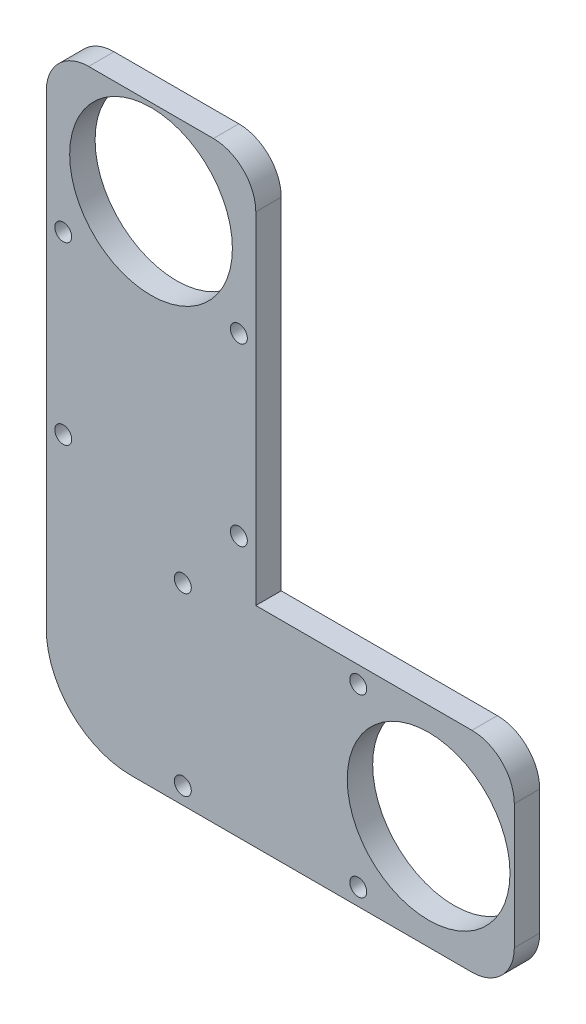
SolidWorks part; units mm, degrees
ref_plane "前视基准面" through (0, 0, 0) normal (0, 0, 1) x (1, 0, 0)
ref_plane "上视基准面" through (0, 0, 0) normal (0, 1, 0) x (1, 0, 0)
ref_plane "右视基准面" through (0, 0, 0) normal (1, 0, 0) x (0, 0, -1)
sketch "草图1" plane through (0, 0, 0) normal (0, 0, 1) x (1, 0, 0)
  line L1 (-1.2093, 0.7424) -> (44.0107, 0.7424)
  line L2 (-1.2093, 0.7424) -> (-1.2093, -23.9776)
  line L3 (-1.2093, -23.9776) -> (44.0107, -23.9776)
  line L4 (44.0107, 0.7424) -> (44.0107, -23.9776)
  circle A0 centre (33.9007, -11.6176) radius 9.6
  circle A1 centre (25.6007, -1.2576) radius 1
  circle A2 centre (4.9007, -1.2576) radius 1
  circle A3 centre (4.9007, -21.9776) radius 1
  circle A4 centre (25.6007, -21.9776) radius 1
  dimension "D3" = 19.2
  dimension "D4" = 2
  dimension "D5" = 2
  dimension "D6" = 2
  dimension "D7" = 2
  dimension "D10" = 20.7
  dimension "D11" = 20.7
  dimension "D13" = 2
  dimension "D15" = 2
  dimension "D1" = 45.22
  dimension "D2" = 24.72
  dimension "D8" = 6.11
  dimension "D9" = 6.11
  dimension "D12" = 2
  dimension "D14" = 2
  dimension "D16" = 10.11
  dimension "D17" = 12.36
extrude "凸台-拉伸1" add sketch "草图1" along normal blind 3
sketch "草图2" plane through (-1.2093, 0, 0) normal (-1, 0, 0) x (0, 0, 1)
  line L4 (0, 0.7424) -> (0, -23.9776)
  line L5 (0, -23.9776) -> (3, -23.9776)
  line L6 (3, -23.9776) -> (3, 0.7424)
  line L7 (3, 0.7424) -> (0, 0.7424)
  line L8 (0, 0.7424) -> (0, -23.9776)
  line L9 (0, -23.9776) -> (3, -23.9776)
  line L10 (3, -23.9776) -> (3, 0.7424)
  line L11 (3, 0.7424) -> (0, 0.7424)
  dimension "D1" = 0
extrude "凸台-拉伸2" add sketch "草图2" along normal blind 10
sketch "草图3" plane through (0, 0.7424, 0) normal (0, 1, 0) x (1, 0, 0)
  line L0 (-11.2093, -3) -> (-11.2093, 0) construction
  line L1 (-11.2093, 0) -> (13.5107, 0)
  line L2 (-11.2093, 0) -> (-11.2093, -3)
  line L3 (-11.2093, -3) -> (13.5107, -3)
  line L4 (13.5107, 0) -> (13.5107, -3)
  line L5 (44.0107, 0) -> (-11.2093, 0) construction
  line L6 (44.0107, -3) -> (-11.2093, -3) construction
  dimension "D1" = 24.72
  dimension "D2" = 0
  dimension "D3" = 0
  dimension "D4" = 0
extrude "凸台-拉伸3" add sketch "草图3" along normal blind 45.22
sketch "草图4" plane through (0, 0, 3) normal (0, 0, 1) x (1, 0, 0)
  line L0 (-11.2093, 45.9624) -> (13.5107, 45.9624) construction
  line L1 (-11.2093, -23.9776) -> (-11.2093, 45.9624) construction
  line L2 (13.5107, 45.9624) -> (13.5107, 0.7424) construction
  circle A0 centre (1.1507, 35.8524) radius 9.6
  circle A1 centre (-9.2093, 27.5524) radius 1
  circle A2 centre (11.5107, 27.5524) radius 1
  circle A3 centre (11.5107, 6.8524) radius 1
  circle A4 centre (-9.2093, 6.8524) radius 1
  dimension "D1" = 19.2
  dimension "D2" = 2
  dimension "D3" = 2
  dimension "D4" = 2
  dimension "D5" = 2
  dimension "D7" = 12.36
  dimension "D8" = 2
  dimension "D9" = 2
  dimension "D10" = 2
  dimension "D11" = 2
  dimension "D13" = 20.7
  dimension "D14" = 18.41
  dimension "D15" = 18.41
  dimension "D6" = 10.11
  dimension "D12" = 20.7
extrude "切除-拉伸1" cut sketch "草图4" against normal blind 4
fillet "圆角3" radius 10 1 edges at (-11.2093, -23.9776, 1.5)
fillet "圆角4" radius 5 1 edges at (44.0107, -23.9776, 1.5)
fillet "圆角5" radius 5 1 edges at (44.0107, 0.7424, 1.5)
fillet "圆角6" radius 5 1 edges at (-11.2093, 45.9624, 1.5)
fillet "圆角7" radius 5 1 edges at (13.5107, 45.9624, 1.5)
